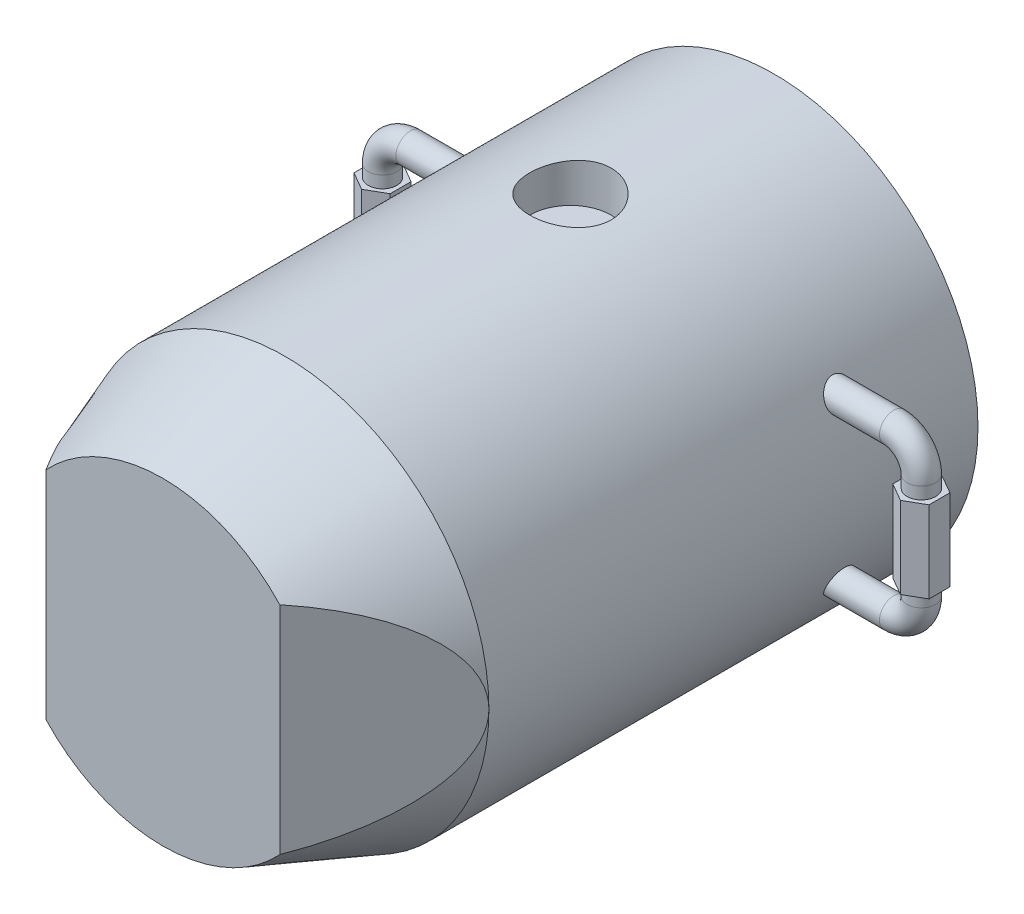
SolidWorks part; units mm, degrees
ref_plane "Ön Düzlem" through (0, 0, 0) normal (0, 0, 1) x (1, 0, 0)
ref_plane "Üst Düzlem" through (0, 0, 0) normal (0, 1, 0) x (1, 0, 0)
ref_plane "Sağ Düzlem" through (0, 0, 0) normal (1, 0, 0) x (0, 0, -1)
sketch "Çizim1" plane through (0, 0, 0) normal (0, 0, 1) x (1, 0, 0)
  circle A0 centre (0, 0) radius 50
  dimension "D1" = 100
extrude "Yükseklik-Ekstrüzyon1" add sketch "Çizim1" along normal blind 150
chamfer "Pah1" distance 30 angle 20 1 edges at (50, 0, 150)
sketch "Çizim5" plane through (0, 0, 0) normal (0, 1, 0) x (1, 0, 0)
  line L0 (-50, -120) -> (-120.0026, -158.0484)
  line L1 (-120.0026, -158.0484) -> (-22.9593, -158.0484)
  line L2 (-22.9593, -158.0484) -> (-50, -120)
  line L3 (0, -11.454) -> (0, -108.3377) construction
  line L4 (22.9593, -158.0484) -> (50, -120)
  line L5 (120.0026, -158.0484) -> (22.9593, -158.0484)
  line L6 (50, -120) -> (120.0026, -158.0484)
  point P12 (-22.9593, -158.0484)
extrude "Kes-Ekstrüzyon1" cut sketch "Çizim5" against normal mid plane 100
ref_plane "Düzlem1" through (0, 0, 30) normal (0, 0, 1) x (1, 0, 0)
sketch "Çizim6" plane through (0, 0, 30) normal (0, 0, 1) x (1, 0, 0)
  line L0 (-44.301, -19.7104) -> (-59.3253, -19.7104)
  line L1 (-66.1045, -12.9312) -> (-66.1045, 12.9312)
  line L2 (-66.1045, 0) -> (-39.9456, 0) construction
  line L3 (-44.301, 19.7104) -> (-59.3253, 19.7104)
  arc A0 (-59.3253, -19.7104) -> (-66.1045, -12.9312) centre (-59.3253, -12.9312) cw
  arc A1 (-59.3253, 19.7104) -> (-66.1045, 12.9312) centre (-59.3253, 12.9312) ccw
sweep "Süpür1" add path "Çizim6" circular profile diameter 7 parameters "D3"=7
mirror "Aynalama1" about plane through (0, 0, 0) normal (1, 0, 0) of "Süpür1"
sketch "Çizim20" plane through (0, 0, 0) normal (0, 1, 0) x (1, 0, 0)
  circle A0 centre (0, -50) radius 10
  dimension "D1" = 20
  dimension "D2" = 50
extrude "Kes-Ekstrüzyon2" cut sketch "Çizim20" against normal blind 100 from offset 40 offset against normal yes
mirror "Aynalama2" about plane through (0, 0, 0) normal (0, 1, 0) of "Kes-Ekstrüzyon2"
sketch "Çizim21" plane through (0, 0, 0) normal (0, 1, 0) x (1, 0, 0)
  line L1 (-66.1045, -35.127) -> (-61.6644, -32.5635)
  line L2 (-61.6644, -32.5635) -> (-61.6644, -27.4365)
  line L3 (-61.6644, -27.4365) -> (-66.1045, -24.873)
  line L4 (-66.1045, -24.873) -> (-70.5446, -27.4365)
  line L5 (-70.5446, -27.4365) -> (-70.5446, -32.5635)
  line L6 (-70.5446, -32.5635) -> (-66.1045, -35.127)
  circle A0 centre (-66.1045, -30) radius 4.4401 construction
extrude "Yükseklik-Ekstrüzyon2" add sketch "Çizim21" along normal mid plane 20
mirror "Aynalama3" about plane through (0, 0, 0) normal (1, 0, 0) of "Yükseklik-Ekstrüzyon2"
